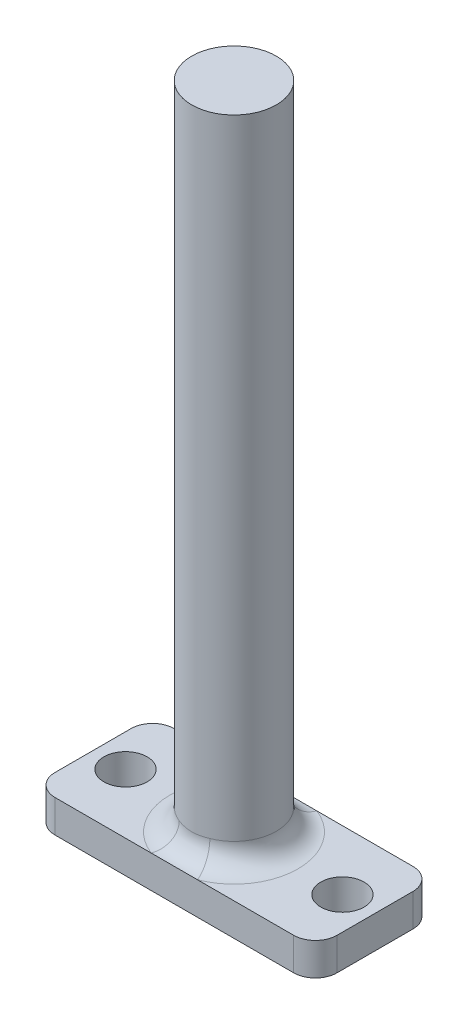
SolidWorks part; units mm, degrees
ref_plane "Front Plane" through (0, 0, 0) normal (0, 0, 1) x (1, 0, 0)
ref_plane "Top Plane" through (0, 0, 0) normal (0, 1, 0) x (1, 0, 0)
ref_plane "Right Plane" through (0, 0, 0) normal (1, 0, 0) x (0, 0, -1)
sketch "Sketch1" plane through (0, 0, 0) normal (0, 1, 0) x (1, 0, 0)
  line L1 (-13.97, -6.985) -> (13.97, -6.985)
  line L2 (-16.51, -4.445) -> (-16.51, 4.445)
  line L3 (-13.97, 6.985) -> (13.97, 6.985)
  line L4 (16.51, -4.445) -> (16.51, 4.445)
  line L5 (-16.51, -6.985) -> (16.51, 6.985) construction
  line L6 (-16.51, 6.985) -> (16.51, -6.985) construction
  arc A0 (-13.97, -6.985) -> (-16.51, -4.445) centre (-13.97, -4.445) cw
  arc A1 (13.97, -6.985) -> (16.51, -4.445) centre (13.97, -4.445) ccw
  arc A2 (13.97, 6.985) -> (16.51, 4.445) centre (13.97, 4.445) cw
  arc A3 (-16.51, 4.445) -> (-13.97, 6.985) centre (-13.97, 4.445) cw
  circle A4 centre (-12.7, 0) radius 2.54
  circle A5 centre (12.7, 0) radius 2.54
  point P0 (0, 0)
  dimension "D3" = 2.54
  dimension "D4" = 25.4
  dimension "D5" = 12.7
  dimension "D6" = 5.08
  dimension "D7" = 5.08
  dimension "D8" = 6.985
  dimension "D9" = 6.985
  dimension "D1" = 33.02
  dimension "D2" = 13.97
extrude "Boss-Extrude1" add sketch "Sketch1" along normal blind 3.81
sketch "Sketch2" plane through (0, 3.81, 0) normal (0, 1, 0) x (1, 0, 0)
  circle A0 centre (0, 0) radius 4.953
  dimension "D1" = 9.906
extrude "Boss-Extrude2" add sketch "Sketch2" along normal blind 76.2
fillet "Fillet1" radius 2.54 1 edges at (0, 3.81, -4.953)
